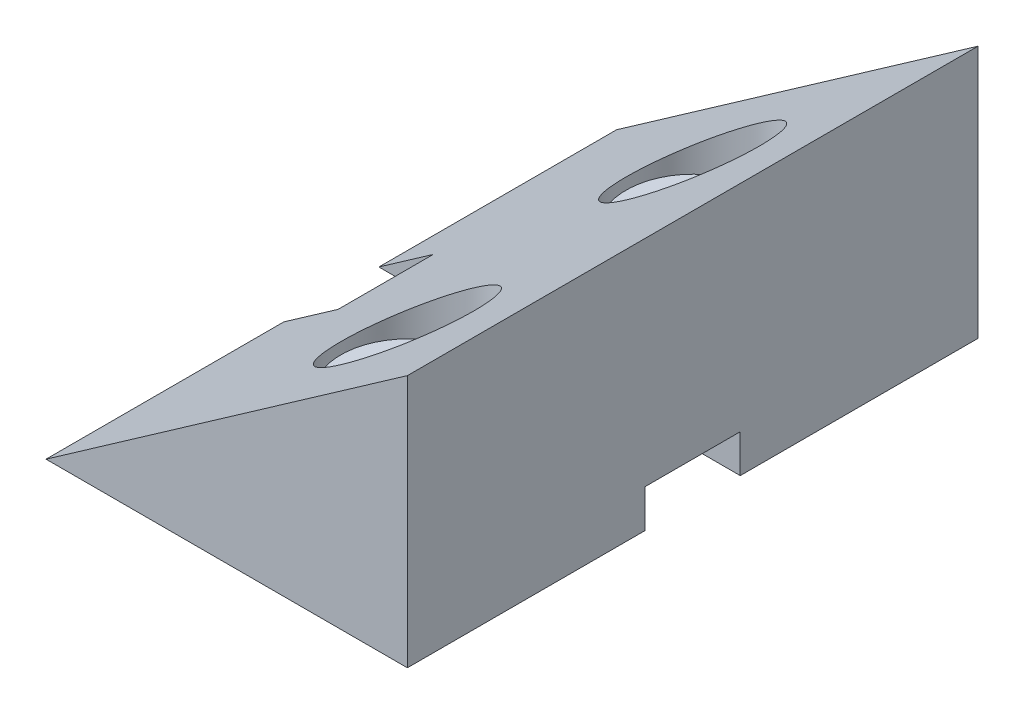
SolidWorks part; units mm, degrees
ref_plane "Plan de face" through (0, 0, 0) normal (0, 0, 1) x (1, 0, 0)
ref_plane "Plan de dessus" through (0, 0, 0) normal (0, 1, 0) x (1, 0, 0)
ref_plane "Plan de droite" through (0, 0, 0) normal (1, 0, 0) x (0, 0, -1)
sketch "Esquisse1" plane through (0, 0, 0) normal (0, 0, 1) x (1, 0, 0)
  line L0 (0, 0) -> (-19, 0)
  line L1 (-19, 0) -> (0, 13.3039)
  line L2 (0, 13.3039) -> (0, 0)
  dimension "D1" = 19
  dimension "D2" = 35
extrude "Boss.-Extru.1" add sketch "Esquisse1" along normal blind 30
ref_plane "Plan1" through (0, 5, 0) normal (0, -1, 0) x (-1, 0, 0)
sketch "Esquisse2" plane through (0, 5, 0) normal (0, -1, 0) x (-1, 0, 0)
  line L0 (0, -30) -> (0, 0) construction
  line L1 (0, -30) -> (0, 0) construction
  line L2 (19, -30) -> (19, 0) construction
  line L3 (0, -30) -> (0, 0) construction
  line L4 (19, -30) -> (19, 0) construction
  line L5 (19, -15) -> (0, -15) construction
  line L6 (19, -30) -> (0, -30) construction
  line L7 (19, 0) -> (0, 0) construction
  line L8 (19, -30) -> (0, -30) construction
  line L9 (19, 0) -> (0, 0) construction
  line L10 (7.5, -15) -> (7.5, 0) construction
  line L11 (7.5, -15) -> (7.5, -30) construction
  circle A0 centre (7.5, -7.5) radius 3.5
  circle A1 centre (7.5, -22.5) radius 3.5
  point P18 (7.5, -22.5)
  point P21 (7.5, -7.5)
  dimension "D1" = 7
  dimension "D2" = 7.5
extrude "Enlèv. mat.-Extru.1" cut sketch "Esquisse2" against normal up to next
sketch "Esquisse3" plane through (0, 5, 0) normal (0, 1, 0) x (1, 0, 0)
  circle A0 centre (-7.5, -7.5) radius 1.75
  circle A1 centre (-7.5, -22.5) radius 1.75
  dimension "D1" = 3.5
extrude "Enlèv. mat.-Extru.2" cut sketch "Esquisse3" against normal up to next contours A1 | A0
sketch "Esquisse4" plane through (0, 0, 0) normal (1, 0, 0) x (0, 0, -1)
  line L0 (-30, 0) -> (0, 0) construction
  line L1 (-17.5, 2) -> (-12.5, 2)
  line L2 (-17.5, 2) -> (-17.5, 0)
  line L3 (-17.5, 0) -> (-12.5, 0)
  line L4 (-12.5, 2) -> (-12.5, 0)
  point P6 (-15, 0)
  point P7 (-15, 0)
  dimension "D1" = 2
  dimension "D2" = 5
extrude "Enlèv. mat.-Extru.3" cut sketch "Esquisse4" against normal up to next
